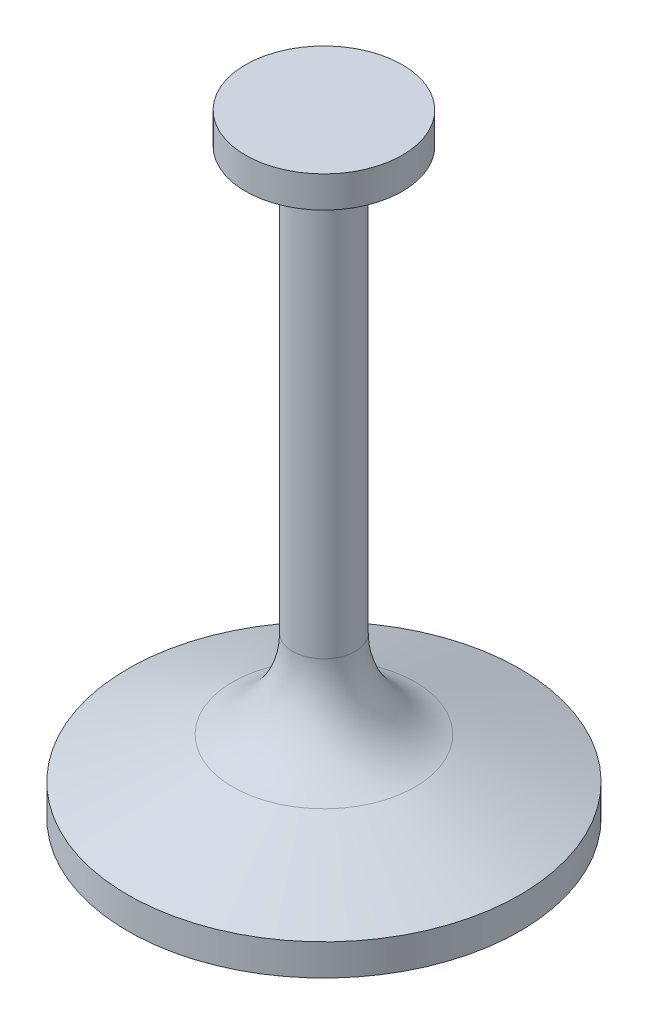
SolidWorks part; units mm, degrees
ref_plane "Front Plane" through (0, 0, 0) normal (0, 0, 1) x (1, 0, 0)
ref_plane "Top Plane" through (0, 0, 0) normal (0, 1, 0) x (1, 0, 0)
ref_plane "Right Plane" through (0, 0, 0) normal (1, 0, 0) x (0, 0, -1)
sketch "Sketch1" plane through (0, 0, 0) normal (0, 0, 1) x (1, 0, 0)
  line L0 (0, 96.4658) -> (0, 990.6)
  line L1 (0, 990.6) -> (127, 990.6)
  line L2 (127, 990.6) -> (127, 939.8)
  line L3 (127, 939.8) -> (50.8, 939.8)
  line L4 (50.8, 939.8) -> (50.8, 152.4)
  line L5 (50.8, 152.4) -> (317.5, 47.9495)
  line L6 (317.5, 47.9495) -> (317.5, -2.8505)
  line L7 (317.5, -2.8505) -> (266.7, -2.8505)
  arc A0 (0, 96.4658) -> (266.7, -2.8505) centre (-262.4286, -1016) cw
  point P3 (-373.2789, 536.3882)
  point P10 (0, 0)
  point P14 (0, 0)
  point P15 (0, 0)
  point P16 (0, 436.5102)
  point P17 (0, 132.7052)
  point P18 (0, 0)
  point P19 (0, 0)
  dimension "D9" = 1143
  dimension "D1" = 50.8
  dimension "D2" = 990.6
  dimension "D3" = 127
  dimension "D4" = 76.2
  dimension "D5" = 50.8
  dimension "D6" = 50.8
  dimension "D7" = 317.5
  dimension "D8" = 1016
  dimension "D10" = 152.4
revolve "Revolve1" add sketch "Sketch1" angle 360 about L0
fillet "Fillet1" radius 152.4 1 edges at (0, 152.4, -50.8)
